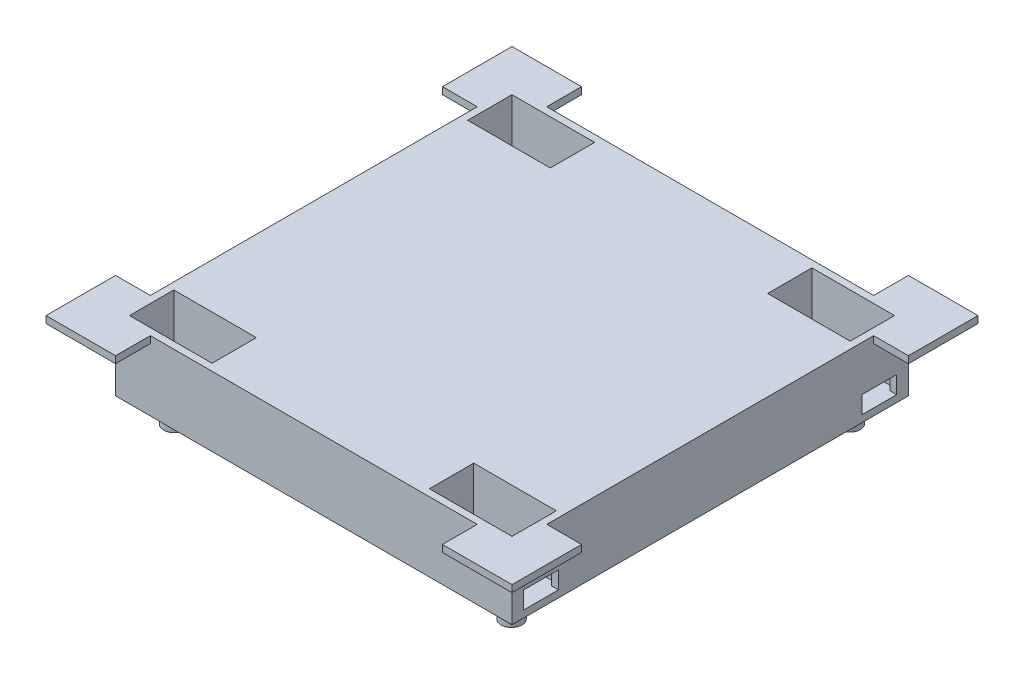
SolidWorks part; units mm, degrees
ref_plane "Front Plane" through (0, 0, 0) normal (0, 0, 1) x (1, 0, 0)
ref_plane "Top Plane" through (0, 0, 0) normal (0, 1, 0) x (1, 0, 0)
ref_plane "Right Plane" through (0, 0, 0) normal (1, 0, 0) x (0, 0, -1)
sketch "Sketch1" plane through (0, 0, 0) normal (0, 1, 0) x (1, 0, 0)
  line L0 (0, 60) -> (0, -60) construction
  line L5 (-60, -60) -> (60, -60)
  line L6 (-60, -60) -> (-60, 60)
  line L7 (-60, 60) -> (60, 60)
  line L8 (60, -60) -> (60, 60)
  line L9 (-60, -60) -> (60, 60) construction
  line L10 (-60, 60) -> (60, -60) construction
  line L25 (-60, 0) -> (60, 0) construction
  point P0 (0, 0)
  dimension "D1" = 120
  dimension "D2" = 120
extrude "Boss-Extrude1" add sketch "Sketch1" along normal blind 2 and the other way blind 3
sketch "Sketch3" plane through (0, 0, 0) normal (0, 1, 0) x (1, 0, 0)
  line L0 (-60, -60) -> (60, -60) construction
  line L1 (-57, -57) -> (-29.25, -57)
  line L2 (-57, -57) -> (-57, -40.25)
  line L3 (-57, -40.25) -> (-29.25, -40.25)
  line L4 (-29.25, -57) -> (-29.25, -40.25)
  line L5 (-57, -57) -> (-29.25, -40.25) construction
  line L6 (-57, -40.25) -> (-29.25, -57) construction
  line L7 (-60, -60) -> (-60, 60) construction
  line L8 (0, 60) -> (0, -60) construction
  line L9 (-60, 60) -> (60, 60) construction
  line L10 (60, 0) -> (-60, 0) construction
  line L12 (60, -60) -> (60, 60) construction
  line L13 (57, -57) -> (29.25, -40.25) construction
  line L14 (57, -40.25) -> (29.25, -57) construction
  line L15 (57, -57) -> (29.25, -57)
  line L16 (29.25, -57) -> (29.25, -40.25)
  line L17 (57, -40.25) -> (29.25, -40.25)
  line L18 (57, -57) -> (57, -40.25)
  line L19 (57, 40.25) -> (29.25, 57) construction
  line L20 (57, 57) -> (29.25, 40.25) construction
  line L21 (-57, 40.25) -> (-29.25, 57) construction
  line L22 (-57, 57) -> (-29.25, 40.25) construction
  line L23 (57, 57) -> (57, 40.25)
  line L24 (57, 40.25) -> (29.25, 40.25)
  line L25 (29.25, 57) -> (29.25, 40.25)
  line L26 (57, 57) -> (29.25, 57)
  line L27 (-29.25, 57) -> (-29.25, 40.25)
  line L28 (-57, 40.25) -> (-29.25, 40.25)
  line L29 (-57, 57) -> (-57, 40.25)
  line L30 (-57, 57) -> (-29.25, 57)
  point P0 (-43.125, -48.625)
  point P17 (43.125, -48.625)
  point P30 (43.125, 48.625)
  point P31 (-43.125, 48.625)
  dimension "D1" = 3
  dimension "D2" = 3
  dimension "D3" = 16.75
  dimension "27.75" = 27.75
extrude "Boss-Extrude4" add sketch "Sketch3" against normal blind 18
ref_plane "Plane3" through (0, 2, 0) normal (0, 1, 0) x (1, 0, 0)
sketch "Sketch4" plane through (0, 2, 0) normal (0, 1, 0) x (1, 0, 0)
  line L0 (-60, 0) -> (60, 0) construction
  line L1 (-60, -60) -> (-60, 60) construction
  line L2 (60, -60) -> (60, 60) construction
  line L3 (0, 60) -> (0, -60) construction
  line L4 (-60, 60) -> (60, 60) construction
  line L5 (-60, -60) -> (60, -60) construction
  line L6 (55, -55) -> (31.25, -42.25) construction
  line L7 (-55, -55) -> (-31.25, -55)
  line L8 (-55, -55) -> (-55, -42.25)
  line L9 (-55, -42.25) -> (-31.25, -42.25)
  line L10 (-31.25, -55) -> (-31.25, -42.25)
  line L11 (-55, -55) -> (-31.25, -42.25) construction
  line L12 (-55, -42.25) -> (-31.25, -55) construction
  line L13 (55, -42.25) -> (31.25, -55) construction
  line L14 (55, -42.25) -> (31.25, -42.25)
  line L15 (31.25, -55) -> (31.25, -42.25)
  line L16 (55, -55) -> (31.25, -55)
  line L17 (55, -55) -> (55, -42.25)
  line L18 (55, 42.25) -> (31.25, 55) construction
  line L19 (-55, 42.25) -> (-31.25, 55) construction
  line L20 (-55, 55) -> (-31.25, 42.25) construction
  line L21 (55, 55) -> (31.25, 42.25) construction
  line L22 (55, 55) -> (55, 42.25)
  line L23 (55, 55) -> (31.25, 55)
  line L24 (31.25, 55) -> (31.25, 42.25)
  line L25 (55, 42.25) -> (31.25, 42.25)
  line L26 (-31.25, 55) -> (-31.25, 42.25)
  line L27 (-55, 42.25) -> (-31.25, 42.25)
  line L28 (-55, 55) -> (-55, 42.25)
  line L29 (-55, 55) -> (-31.25, 55)
  point P13 (-43.125, -48.625)
  point P18 (43.125, -48.625)
  point P31 (43.125, 48.625)
  point P32 (-43.125, 48.625)
  dimension "D1" = 5
  dimension "D2" = 5
  dimension "D3" = 12.75
  dimension "D4" = 23.75
extrude "Cut-Extrude1" cut sketch "Sketch4" against normal blind 18
ref_plane "Plane4" through (0, -18, 0) normal (0, -1, 0) x (-1, 0, 0)
sketch "Sketch5" plane through (0, -18, 0) normal (0, -1, 0) x (-1, 0, 0)
  line L0 (0, -60) -> (0, 60) construction
  line L1 (60, -60) -> (-60, -60) construction
  line L2 (60, 60) -> (-60, 60) construction
  line L3 (-60, 0) -> (60, 0) construction
  line L4 (-60, -60) -> (-60, 60) construction
  line L5 (60, -60) -> (60, 60) construction
  line L6 (57, -40.25) -> (57, -57) construction
  line L7 (57, -57) -> (29.25, -57) construction
  circle A0 centre (48.5, -48.625) radius 3
  circle A1 centre (-48.5, -48.625) radius 3
  circle A2 centre (48.5, 48.625) radius 3
  circle A3 centre (-48.5, 48.625) radius 3
  dimension "D1" = 8.5
  dimension "D2" = 8.375
extrude "Boss-Extrude5" add sketch "Sketch5" along normal blind 7
ref_plane "Plane5" through (57, 0, 0) normal (1, 0, 0) x (0, 0, -1)
sketch "Sketch6" plane through (57, 0, 0) normal (1, 0, 0) x (0, 0, -1)
  line L1 (-53.625, -16) -> (-43.625, -16)
  line L2 (-53.625, -16) -> (-53.625, -11)
  line L3 (-53.625, -11) -> (-43.625, -11)
  line L4 (-43.625, -16) -> (-43.625, -11)
  line L5 (-53.625, -16) -> (-43.625, -11) construction
  line L6 (-53.625, -11) -> (-43.625, -16) construction
  line L10 (-57, -18) -> (-57, -3) construction
  line L11 (0, 0) -> (0, -36.0258) construction
  line L12 (53.625, -11) -> (43.625, -11)
  line L13 (43.625, -16) -> (43.625, -11)
  line L14 (53.625, -16) -> (43.625, -16)
  line L15 (53.625, -16) -> (53.625, -11)
  line L17 (-57, -18) -> (-40.25, -18) construction
  point P0 (-48.625, -13.5)
  dimension "D1" = 5
  dimension "D2" = 10
  dimension "D3" = 2
  dimension "D4" = 3.375
extrude "Cut-Extrude2" cut sketch "Sketch6" against normal blind 2
ref_plane "Plane6" through (-57, 0, 0) normal (-1, 0, 0) x (0, 0, 1)
sketch "Sketch7" plane through (-57, 0, 0) normal (-1, 0, 0) x (0, 0, 1)
  line L0 (0, 0) -> (0, -43.3376) construction
  line L6 (53.625, -16) -> (53.625, -11)
  line L7 (53.625, -11) -> (43.625, -11)
  line L8 (43.625, -16) -> (43.625, -11)
  line L9 (-43.625, -16) -> (-43.625, -11)
  line L10 (-53.625, -11) -> (-43.625, -11)
  line L11 (-53.625, -16) -> (-53.625, -11)
  line L12 (-53.625, -16) -> (-43.625, -16)
  line L14 (43.625, -16) -> (53.625, -16)
extrude "Cut-Extrude3" cut sketch "Sketch7" against normal blind 2
ref_plane "Plane15" through (-29.25, 0, 0) normal (1, 0, 0) x (0, 0, -1)
sketch "Sketch9" plane through (-29.25, 0, 0) normal (1, 0, 0) x (0, 0, -1)
  line L5 (0, -22.0213) -> (0, 27.4105) construction
  line L11 (57, -3) -> (55, -3)
  line L12 (57, -3) -> (57, -18)
  line L22 (57, -18) -> (56.5, -18)
  line L23 (40.25, -18) -> (57, -18) construction
  line L24 (56.5, -18) -> (55, -3)
  line L25 (-56.5, -18) -> (-55, -3)
  line L26 (-57, -18) -> (-56.5, -18)
  line L27 (-57, -3) -> (-57, -18)
  line L28 (-57, -3) -> (-55, -3)
  dimension "D1" = 2
extrude "Boss-Extrude6" add sketch "Sketch9" along normal up to next
ref_plane "Plane16" through (0, 0, -40.25) normal (0, 0, 1) x (1, 0, 0)
sketch "Sketch10" plane through (0, 0, -40.25) normal (0, 0, 1) x (1, 0, 0)
  line L0 (-57, -18) -> (-29.25, -18) construction
  line L1 (-57, -3) -> (-54, -3)
  line L2 (-57, -3) -> (-57, -18)
  line L3 (-57, -18) -> (-56.5, -18)
  line L4 (-54, -3) -> (-56.5, -18)
  line L5 (0, 0) -> (0, -25.1074) construction
  line L10 (54, -3) -> (56.5, -18)
  line L11 (57, -18) -> (56.5, -18)
  line L12 (57, -3) -> (57, -18)
  line L13 (57, -3) -> (54, -3)
  dimension "D1" = 0.5
  dimension "D2" = 3
extrude "Boss-Extrude7" add sketch "Sketch10" along normal up to next
sketch "Sketch12" plane through (0, 0, 60) normal (0, 0, 1) x (1, 0, 0)
  line L1 (60, 2) -> (-60, 2)
  line L2 (60, 2) -> (60, -3)
  line L3 (60, -3) -> (-60, -3)
  line L4 (-60, 2) -> (-60, -3)
extrude "Cut-Extrude4" cut sketch "Sketch12" against normal blind 3
sketch "Sketch13" plane through (0, 0, -60) normal (0, 0, -1) x (-1, 0, 0)
  line L1 (-60, -3) -> (60, -3)
  line L2 (-60, -3) -> (-60, 2)
  line L3 (-60, 2) -> (60, 2)
  line L4 (60, -3) -> (60, 2)
extrude "Cut-Extrude5" cut sketch "Sketch13" against normal blind 3
sketch "Sketch14" plane through (-60, 0, 0) normal (-1, 0, 0) x (0, 0, 1)
  line L1 (-57, -3) -> (57, -3)
  line L2 (-57, -3) -> (-57, 2)
  line L3 (-57, 2) -> (57, 2)
  line L4 (57, -3) -> (57, 2)
extrude "Cut-Extrude6" cut sketch "Sketch14" against normal blind 3
sketch "Sketch15" plane through (60, 0, 0) normal (1, 0, 0) x (0, 0, -1)
  line L1 (57, 2) -> (-57, 2)
  line L2 (57, 2) -> (57, -3)
  line L3 (57, -3) -> (-57, -3)
  line L4 (-57, 2) -> (-57, -3)
extrude "Cut-Extrude7" cut sketch "Sketch15" against normal blind 3
sketch "Sketch16" plane through (0, 0, 0) normal (0, 1, 0) x (1, 0, 0)
  line L0 (-57, 47) -> (-67, 47)
  line L1 (-57, -57) -> (-57, 57) construction
  line L2 (-67, 47) -> (-67, 67)
  line L3 (-67, 67) -> (-47, 67)
  line L4 (-47, 67) -> (-47, 57)
  line L5 (-57, 57) -> (57, 57) construction
  line L6 (0, 0) -> (0, 30.5156) construction
  line L7 (0, 0) -> (26.5462, 0) construction
  line L8 (-57, 47) -> (-57, 57)
  line L9 (-57, 57) -> (-47, 57)
  line L10 (57, 47) -> (57, 57)
  line L11 (67, 47) -> (67, 67)
  line L12 (57, 47) -> (67, 47)
  line L13 (57, 57) -> (47, 57)
  line L14 (47, 67) -> (47, 57)
  line L15 (67, 67) -> (47, 67)
  line L16 (67, -67) -> (47, -67)
  line L17 (47, -67) -> (47, -57)
  line L18 (57, -57) -> (47, -57)
  line L19 (57, -47) -> (67, -47)
  line L20 (67, -47) -> (67, -67)
  line L21 (57, -47) -> (57, -57)
  line L22 (-57, -57) -> (-47, -57)
  line L23 (-57, -47) -> (-57, -57)
  line L24 (-47, -67) -> (-47, -57)
  line L25 (-67, -67) -> (-47, -67)
  line L26 (-67, -47) -> (-67, -67)
  line L27 (-57, -47) -> (-67, -47)
  dimension "D1" = 10
  dimension "D2" = 10
  dimension "D3" = 20
  dimension "D4" = 20
extrude "Boss-Extrude8" add sketch "Sketch16" along normal blind 2
